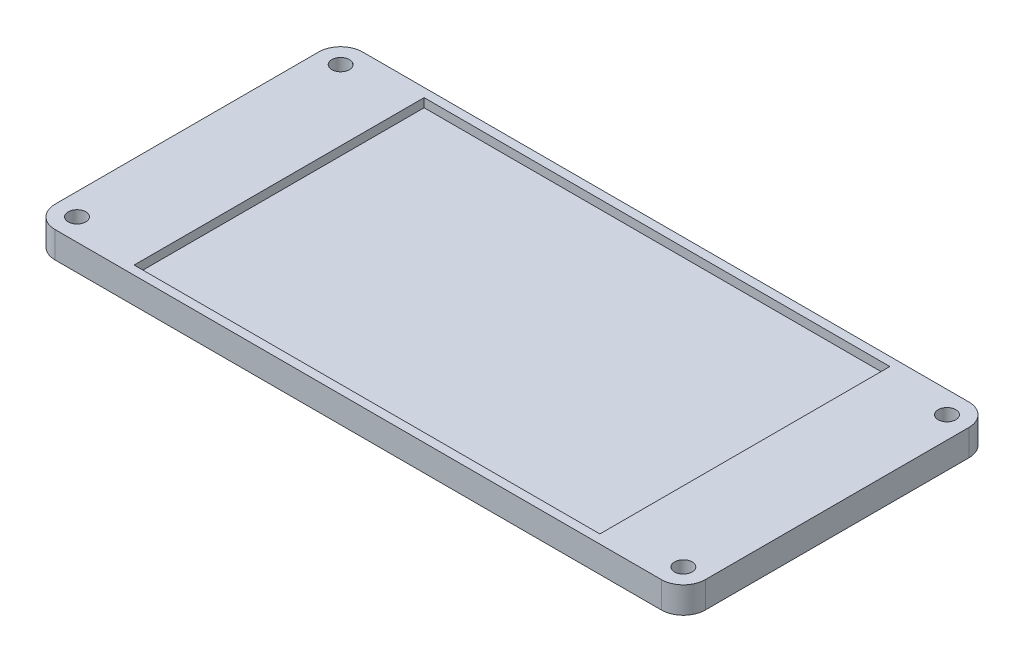
SolidWorks part; units mm, degrees
ref_plane "Płaszczyzna przednia" through (0, 0, 0) normal (0, 0, 1) x (1, 0, 0)
ref_plane "Płaszczyzna górna" through (0, 0, 0) normal (0, 1, 0) x (1, 0, 0)
ref_plane "Płaszczyzna prawa" through (0, 0, 0) normal (1, 0, 0) x (0, 0, -1)
sketch "Szkic1" plane through (0, 0, 0) normal (0, 1, 0) x (1, 0, 0)
  line L1 (-37, -17.5) -> (37, -17.5)
  line L2 (-37, -17.5) -> (-37, 17.5)
  line L3 (-37, 17.5) -> (37, 17.5)
  line L4 (37, -17.5) -> (37, 17.5)
  line L5 (-37, -17.5) -> (37, 17.5) construction
  line L6 (-37, 17.5) -> (37, -17.5) construction
  point P0 (0, 0)
  dimension "D1" = 74
  dimension "D2" = 35
extrude "Dodanie-wyciągnięcie1" add sketch "Szkic1" along normal blind 3
sketch "Szkic2" plane through (0, 3, 0) normal (0, 1, 0) x (1, 0, 0)
  line L1 (-26.5, -16.5) -> (26.5, -16.5)
  line L2 (-26.5, -16.5) -> (-26.5, 16.5)
  line L3 (-26.5, 16.5) -> (26.5, 16.5)
  line L4 (26.5, -16.5) -> (26.5, 16.5)
  line L5 (-26.5, -16.5) -> (26.5, 16.5) construction
  line L6 (-26.5, 16.5) -> (26.5, -16.5) construction
  point P0 (0, 0)
  dimension "D1" = 53
  dimension "D2" = 33
extrude "Wytnij-wyciągnięcie1" cut sketch "Szkic2" against normal blind 1
sketch "Szkic4" plane through (0, 3, 0) normal (0, 1, 0) x (1, 0, 0)
  line L0 (-37, 17.5) -> (-37, 15) construction
  line L1 (-37, 17.5) -> (-37, -17.5) construction
  line L2 (-37, 15) -> (-34.5, 15) construction
  circle A0 centre (-34.5, 15) radius 1
  point P7 (-34.6728, 15.0906)
  dimension "D1" = 2
  dimension "D2" = 2.5
  dimension "D3" = 2.5
extrude "Wytnij-wyciągnięcie2" cut sketch "Szkic4" against normal through all
fillet "Zaokrąglenie1" radius 2.5 4 edges at (-37, 1.5, 17.5) (-37, 1.5, -17.5) (37, 1.5, -17.5) (37, 1.5, 17.5)
mirror "Lustro1" about plane through (0, 0, 0) normal (0, 0, 1) of "Wytnij-wyciągnięcie2"
mirror "Lustro2" about plane through (0, 0, 0) normal (1, 0, 0) of "Lustro1", "Wytnij-wyciągnięcie2"
